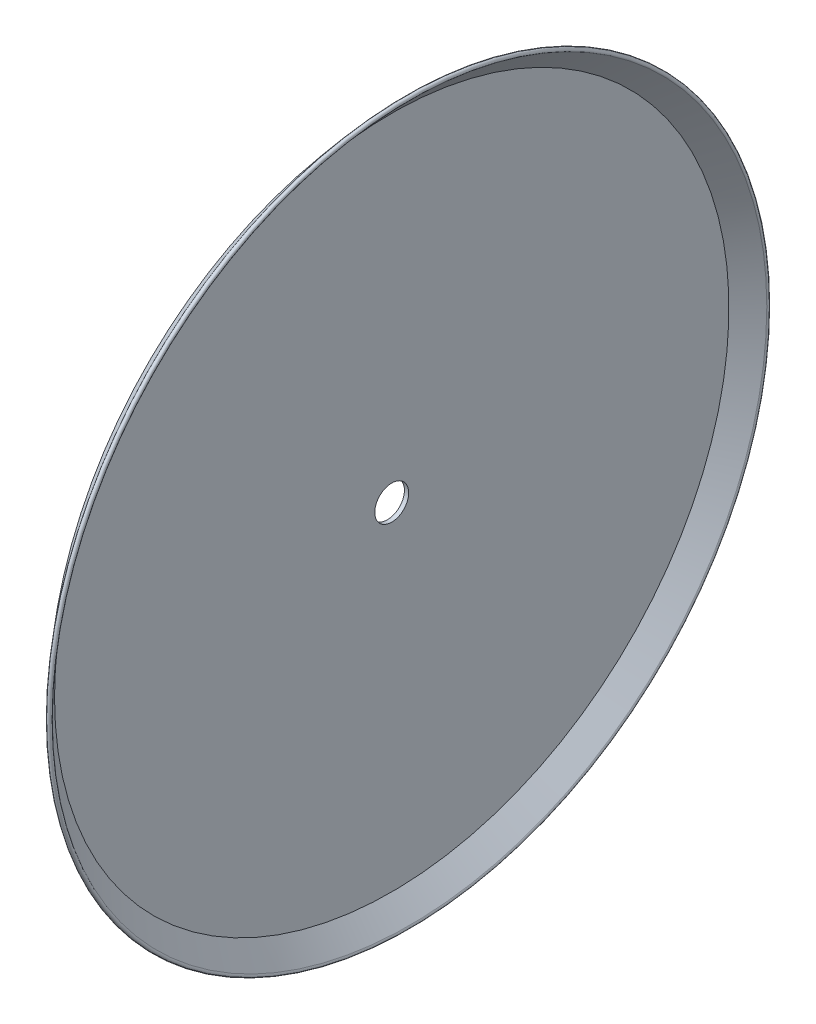
SolidWorks part; units mm, degrees
ref_plane "Front Plane" through (0, 0, 0) normal (0, 0, 1) x (1, 0, 0)
ref_plane "Top Plane" through (0, 0, 0) normal (0, 1, 0) x (1, 0, 0)
ref_plane "Right Plane" through (0, 0, 0) normal (1, 0, 0) x (0, 0, -1)
sketch "Sketch1" plane through (0, 0, 0) normal (0, 0, 1) x (1, 0, 0)
  line L0 (0, 0) -> (-148.0369, 0) construction
  line L8 (-57.0129, 0) -> (-57.0129, 79.7571)
  line L14 (-56.0129, 0) -> (-56.0129, 79.6017)
  line L17 (-57.0129, 0) -> (-56.0129, 0)
  line L18 (-57.0129, 79.7571) -> (-56.8475, 80.2764) construction
  line L19 (-56.0129, 79.6017) -> (-55.9611, 79.7643) construction
  line L20 (-56.8475, 80.2764) -> (-52.5403, 85) construction
  line L21 (-55.9611, 79.7643) -> (-51.8014, 84.3262) construction
  line L22 (-57.0129, 79.7571) -> (-52.5403, 85)
  line L23 (-56.0129, 79.6017) -> (-51.8014, 84.3262)
  arc A3 (-52.5403, 85) -> (-51.8014, 84.3262) centre (-52.1708, 84.6631) cw
  dimension "D1" = 170
  dimension "D2" = 1
revolve "Revolve2" add sketch "Sketch1" angle 360 about L17
sketch "Sketch3" plane through (-56.0129, 0, 0) normal (1, 0, 0) x (0, 0, -1)
  circle A0 centre (0, 0) radius 4
  dimension "D1" = 8
extrude "Cut-Extrude2" cut sketch "Sketch3" against normal blind 10
